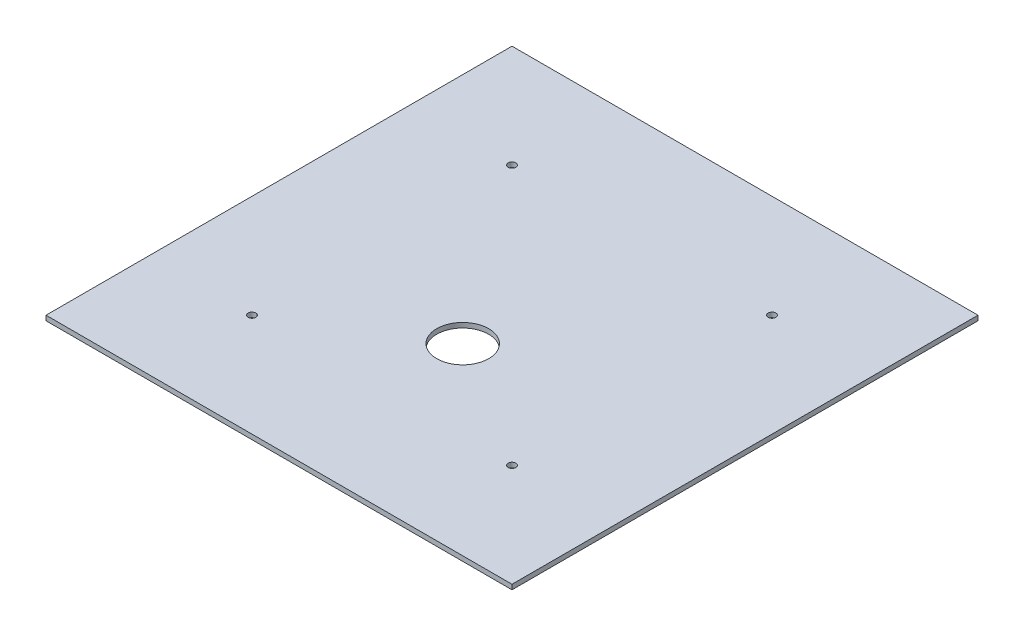
SolidWorks part; units mm, degrees
material "MDF"
ref_plane "Front Plane" through (0, 0, 0) normal (0, 0, 1) x (1, 0, 0)
ref_plane "Top Plane" through (0, 0, 0) normal (0, 1, 0) x (1, 0, 0)
ref_plane "Right Plane" through (0, 0, 0) normal (1, 0, 0) x (0, 0, -1)
sketch "Sketch2" plane through (0, 0, 0) normal (0, 1, 0) x (1, 0, 0)
  line L1 (-152.4, -152.4) -> (152.4, -152.4)
  line L2 (-152.4, -152.4) -> (-152.4, 152.4)
  line L3 (-152.4, 152.4) -> (152.4, 152.4)
  line L4 (152.4, -152.4) -> (152.4, 152.4)
  line L5 (-152.4, -152.4) -> (152.4, 152.4) construction
  line L6 (-152.4, 152.4) -> (152.4, -152.4) construction
  point P0 (0, 0)
  dimension "D1" = 304.8
  dimension "D2" = 304.8
extrude "Boss-Extrude1" add sketch "Sketch2" along normal blind 3.175
sketch "Sketch3" plane through (0, 3.175, 0) normal (0, 1, 0) x (1, 0, 0)
  line L0 (-85.035, 85.035) -> (85.035, 85.035) construction
  line L1 (85.035, 85.035) -> (85.035, -85.035) construction
  line L2 (85.035, -85.035) -> (-85.035, -85.035) construction
  line L3 (-85.035, -85.035) -> (-85.035, 85.035) construction
  line L4 (152.4, 152.4) -> (-152.4, 152.4) construction
  line L5 (152.4, -152.4) -> (152.4, 152.4) construction
  circle A4 centre (-85.035, 85.035) radius 2.5
  circle A5 centre (85.035, 85.035) radius 2.5
  circle A6 centre (-85.035, -85.035) radius 2.5
  circle A7 centre (85.035, -85.035) radius 2.5
  point P4 (0, 85.035)
  point P7 (0, 152.4)
  point P10 (152.4, 0)
  point P11 (85.035, 0)
  dimension "D3" = 5
  dimension "D2" = 170.07
extrude "Cut-Extrude1" cut sketch "Sketch3" against normal through all
sketch "Sketch4" plane through (0, 3.175, 0) normal (0, 1, 0) x (1, 0, 0)
  line L0 (0, -152.4) -> (0, 152.4) construction
  line L1 (-152.4, -152.4) -> (152.4, -152.4) construction
  line L2 (152.4, 152.4) -> (-152.4, 152.4) construction
  circle A0 centre (0, -32.24) radius 17
  dimension "D2" = 34
  dimension "D1" = 120.16
extrude "Cut-Extrude2" cut sketch "Sketch4" against normal through all
